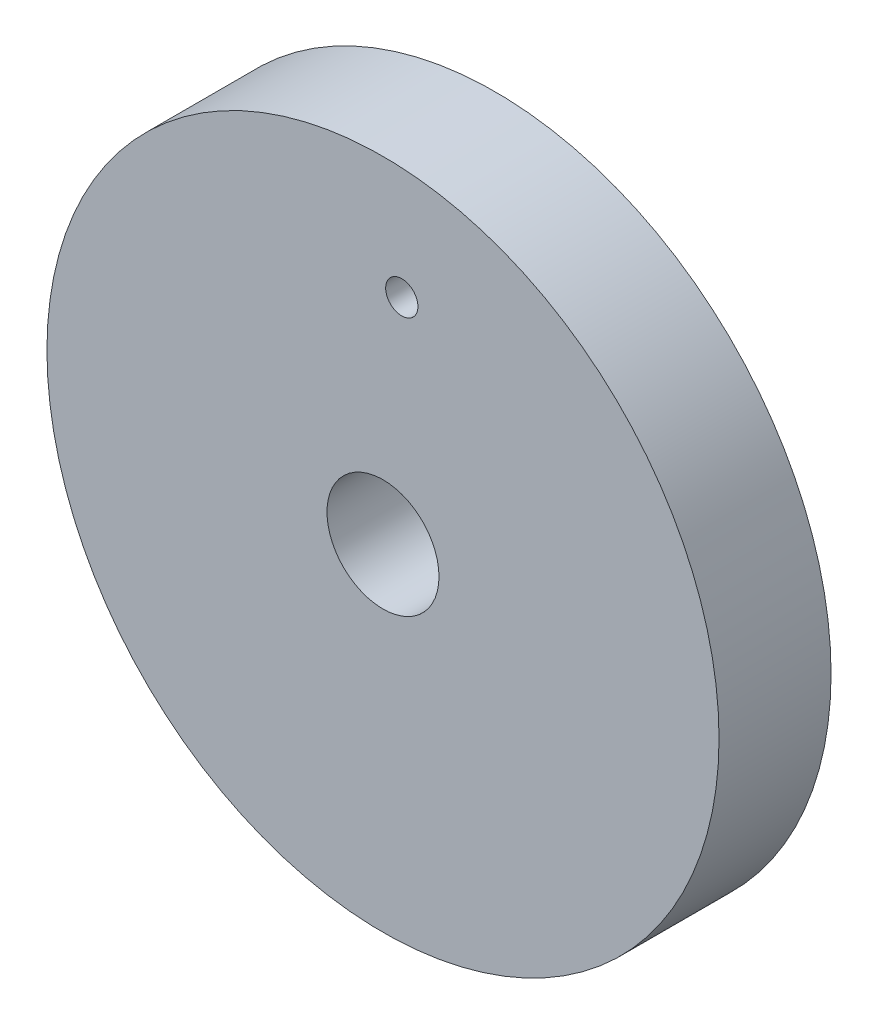
SolidWorks part; units mm, degrees
material "ABS"
ref_plane "Front Plane" through (0, 0, 0) normal (0, 0, 1) x (1, 0, 0)
ref_plane "Top Plane" through (0, 0, 0) normal (0, 1, 0) x (1, 0, 0)
ref_plane "Right Plane" through (0, 0, 0) normal (1, 0, 0) x (0, 0, -1)
sketch "Sketch1" plane through (0, 0, 0) normal (0, 0, 1) x (1, 0, 0)
  circle A0 centre (0, 0) radius 6.35
  circle A1 centre (0, 0) radius 38.1
  dimension "D1" = 12.7
  dimension "D2" = 76.2
extrude "Boss-Extrude1" add sketch "Sketch1" along normal blind 12.7
sketch "Sketch2" plane through (0, 0, 12.7) normal (0, 0, 1) x (1, 0, 0)
  circle A0 centre (2.1304, 25.3196) radius 1.8286
extrude "Cut-Extrude1" cut sketch "Sketch2" against normal through all
